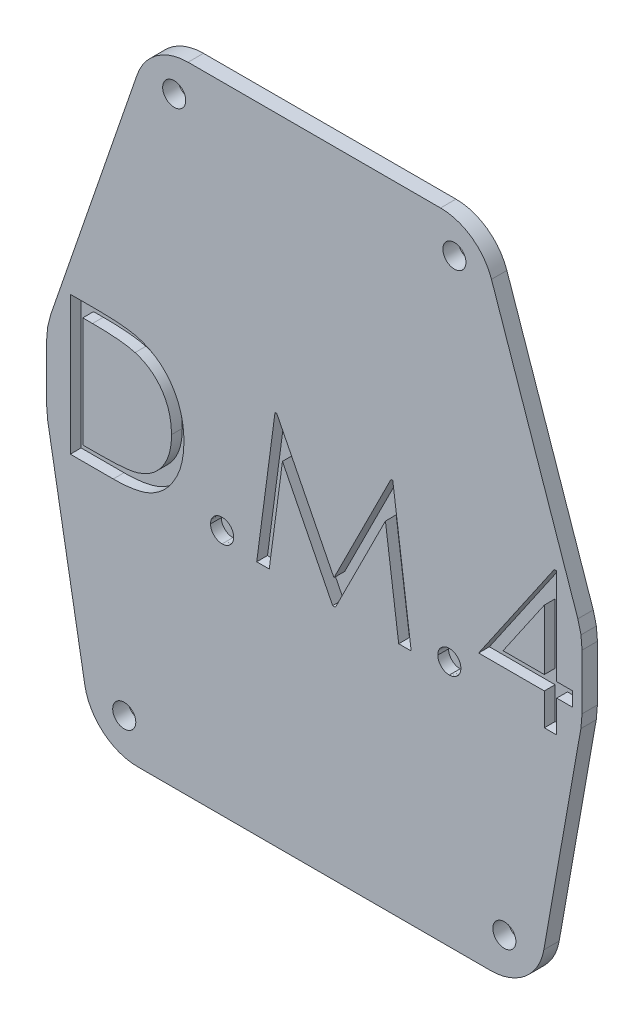
SolidWorks part; units mm, degrees
ref_plane "Front Plane" through (0, 0, 0) normal (0, 0, 1) x (1, 0, 0)
ref_plane "Top Plane" through (0, 0, 0) normal (0, 1, 0) x (1, 0, 0)
ref_plane "Right Plane" through (0, 0, 0) normal (1, 0, 0) x (0, 0, -1)
sketch "Sketch1" plane through (0, 0, 0) normal (0, 0, 1) x (1, 0, 0)
  line L0 (-18.3798, 53.8399) -> (-29.6006, 21.2524)
  line L1 (-29.6006, 21.2524) -> (-30.0083, 19.6472)
  line L2 (-30.0083, 19.6472) -> (-30.1454, 17.9967)
  line L3 (-30.1454, 17.9967) -> (-30.1454, 10.8285)
  line L4 (-30.1454, 10.8285) -> (-29.9935, 9.092)
  line L5 (-29.9935, 9.092) -> (-25.1784, -18.2155)
  line L6 (-18.2848, -24) -> (27.5694, -24)
  line L7 (34.4631, -18.2155) -> (39.2781, 9.092)
  line L8 (39.2781, 9.092) -> (39.43, 10.8285)
  line L9 (39.43, 10.8285) -> (39.43, 17.9967)
  line L10 (39.43, 17.9967) -> (39.2929, 19.6472)
  line L11 (39.2929, 19.6472) -> (38.8852, 21.2524)
  line L12 (38.8852, 21.2524) -> (27.6645, 53.8399)
  line L13 (21.0458, 58.5609) -> (-11.7612, 58.5609)
  arc A2 (-11.7612, 58.5609) -> (-18.3798, 53.8399) centre (-11.7612, 51.5609) ccw
  arc A3 (21.0458, 58.5609) -> (27.6645, 53.8399) centre (21.0458, 51.5609) cw
  arc A4 (27.5694, -24) -> (34.4631, -18.2155) centre (27.5694, -17) ccw
  arc A5 (-25.1784, -18.2155) -> (-18.2848, -24) centre (-18.2848, -17) ccw
  circle A6 centre (-20.0534, -19.1078) radius 1.5
  circle A7 centre (29.338, -19.1078) radius 1.5
  circle A8 centre (22.8456, 54.0841) radius 1.5
  circle A9 centre (-13.561, 54.0841) radius 1.5
extrude "Boss-Extrude1" add sketch "Sketch1" along normal blind 2 contours A9 | L0 L1 L2 L3 L4 L5 A5 L6 A4 L7 L8 L9 L10 L11 L12 A3 L13 A2 | A8 | A7 | A6
sketch "Sketch2" plane through (0, 0, 2) normal (0, 0, 1) x (1, 0, 0)
  text T0 "D.M.4" font "Century Gothic" height in points 68
extrude "Cut-Extrude1" cut sketch "Sketch2" against normal blind 1.4
